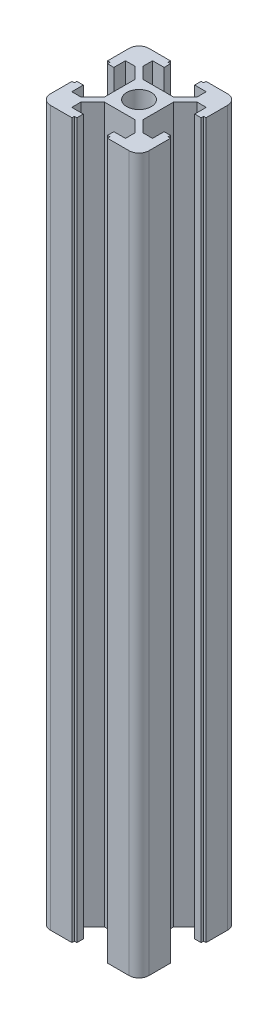
SolidWorks part; units mm, degrees
ref_plane "前视基准面" through (0, 0, 0) normal (0, 0, 1) x (1, 0, 0)
ref_plane "上视基准面" through (0, 0, 0) normal (0, 1, 0) x (1, 0, 0)
ref_plane "右视基准面" through (0, 0, 0) normal (1, 0, 0) x (0, 0, -1)
sketch "草图1" plane through (0, 0, 0) normal (0, 1, 0) x (1, 0, 0)
  line L0 (-6.2985, -5.45) -> (-3.9485, -3.1)
  line L1 (-5.45, -6.2985) -> (-3.1, -3.9485)
  line L2 (-6.2985, -5.45) -> (-8.2, -5.45)
  line L3 (-8.2, -5.45) -> (-8.2, -3.1)
  line L4 (-8.2, -3.1) -> (-10, -3.1)
  line L5 (-10, -3.1) -> (-10, -8)
  line L6 (-8, -10) -> (-3.1, -10)
  line L7 (-5.45, -6.2985) -> (-5.45, -8.2)
  line L8 (-5.45, -8.2) -> (-3.1, -8.2)
  line L9 (-3.1, -8.2) -> (-3.1, -10)
  line L10 (-3.9485, 0) -> (-3.9485, -3.1)
  line L11 (-3.1, -3.9485) -> (0, -3.9485)
  line L12 (-10, -3.6) -> (-9.5, -3.6)
  line L13 (-9.5, -3.6) -> (-9.5, -3.1)
  line L14 (-3.6, -10) -> (-3.6, -9.5)
  line L15 (-3.6, -9.5) -> (-3.1, -9.5)
  line L16 (-3.9485, 0) -> (-2.5, 0) construction
  line L17 (0, -2.5) -> (0, -3.9485) construction
  line L18 (-5.45, 6.2985) -> (-3.1, 3.9485)
  line L19 (-6.2985, 5.45) -> (-3.9485, 3.1)
  line L20 (-5.45, 6.2985) -> (-5.45, 8.2)
  line L21 (-5.45, 8.2) -> (-3.1, 8.2)
  line L22 (-3.1, 8.2) -> (-3.1, 10)
  line L23 (-3.1, 10) -> (-8, 10)
  line L24 (-10, 8) -> (-10, 3.1)
  line L25 (-6.2985, 5.45) -> (-8.2, 5.45)
  line L26 (-8.2, 5.45) -> (-8.2, 3.1)
  line L27 (-8.2, 3.1) -> (-10, 3.1)
  line L28 (-3.1, 3.9485) -> (0, 3.9485)
  line L29 (-3.9485, 3.1) -> (-3.9485, 0)
  line L30 (-3.6, 10) -> (-3.6, 9.5)
  line L31 (-3.6, 9.5) -> (-3.1, 9.5)
  line L32 (-10, 3.6) -> (-9.5, 3.6)
  line L33 (-9.5, 3.6) -> (-9.5, 3.1)
  line L34 (0, 3.9485) -> (0, 2.5) construction
  line L35 (-2.5, 0) -> (-3.9485, 0) construction
  line L36 (6.2985, 5.45) -> (3.9485, 3.1)
  line L37 (5.45, 6.2985) -> (3.1, 3.9485)
  line L38 (6.2985, 5.45) -> (8.2, 5.45)
  line L39 (8.2, 5.45) -> (8.2, 3.1)
  line L40 (8.2, 3.1) -> (10, 3.1)
  line L41 (10, 3.1) -> (10, 8)
  line L42 (8, 10) -> (3.1, 10)
  line L43 (5.45, 6.2985) -> (5.45, 8.2)
  line L44 (5.45, 8.2) -> (3.1, 8.2)
  line L45 (3.1, 8.2) -> (3.1, 10)
  line L46 (3.9485, 0) -> (3.9485, 3.1)
  line L47 (3.1, 3.9485) -> (0, 3.9485)
  line L48 (10, 3.6) -> (9.5, 3.6)
  line L49 (9.5, 3.6) -> (9.5, 3.1)
  line L50 (3.6, 10) -> (3.6, 9.5)
  line L51 (3.6, 9.5) -> (3.1, 9.5)
  line L52 (3.9485, 0) -> (2.5, 0) construction
  line L53 (0, 2.5) -> (0, 3.9485) construction
  line L54 (5.45, -6.2985) -> (3.1, -3.9485)
  line L55 (6.2985, -5.45) -> (3.9485, -3.1)
  line L56 (5.45, -6.2985) -> (5.45, -8.2)
  line L57 (5.45, -8.2) -> (3.1, -8.2)
  line L58 (3.1, -8.2) -> (3.1, -10)
  line L59 (3.1, -10) -> (8, -10)
  line L60 (10, -8) -> (10, -3.1)
  line L61 (6.2985, -5.45) -> (8.2, -5.45)
  line L62 (8.2, -5.45) -> (8.2, -3.1)
  line L63 (8.2, -3.1) -> (10, -3.1)
  line L64 (0, -3.9485) -> (3.1, -3.9485)
  line L65 (3.9485, -3.1) -> (3.9485, 0)
  line L66 (3.6, -10) -> (3.6, -9.5)
  line L67 (3.6, -9.5) -> (3.1, -9.5)
  line L68 (10, -3.6) -> (9.5, -3.6)
  line L69 (9.5, -3.6) -> (9.5, -3.1)
  line L70 (0, -3.9485) -> (0, -2.5) construction
  line L71 (2.5, 0) -> (3.9485, 0) construction
  line L72 (0, 3.9485) -> (-3.1, 3.9485) [skipped]
  circle A0 centre (0, 0) radius 2.5
  arc A1 (-10, -8) -> (-8, -10) centre (-8, -8) ccw
  arc A3 (-8, 10) -> (-10, 8) centre (-8, 8) ccw
  arc A5 (10, 8) -> (8, 10) centre (8, 8) ccw
  arc A7 (8, -10) -> (10, -8) centre (8, -8) ccw
  point P25 (-10, -10)
  point P98 (0, 0)
  dimension "D9" = 2
  dimension "D15" = 5
  dimension "D2" = 1.2
  dimension "D4" = 5.45
  dimension "D5" = 1.8
  dimension "D6" = 3.1
  dimension "D7" = 135
  dimension "D10" = 0.5
  dimension "D11" = 0.5
  dimension "D12" = 0.5
  dimension "D13" = 0.5
  dimension "D14" = 4
extrude "凸台-拉伸1" add sketch "草图1" along normal blind 145 contours L59 A7 L60 L68 L69 L63 L62 L61 L55 L65 L46 L36 L38 L39 L40 L49 L48 L41 A5 L42 L50 L51 L45 L44 L43 L37 L47 L28 L18 L20 L21 L22 L31 L30 L23 A3 L24 L32 L33 L27 L26 L25 L19 L29 L10 L0 L2 L3 L4 L13 L12
